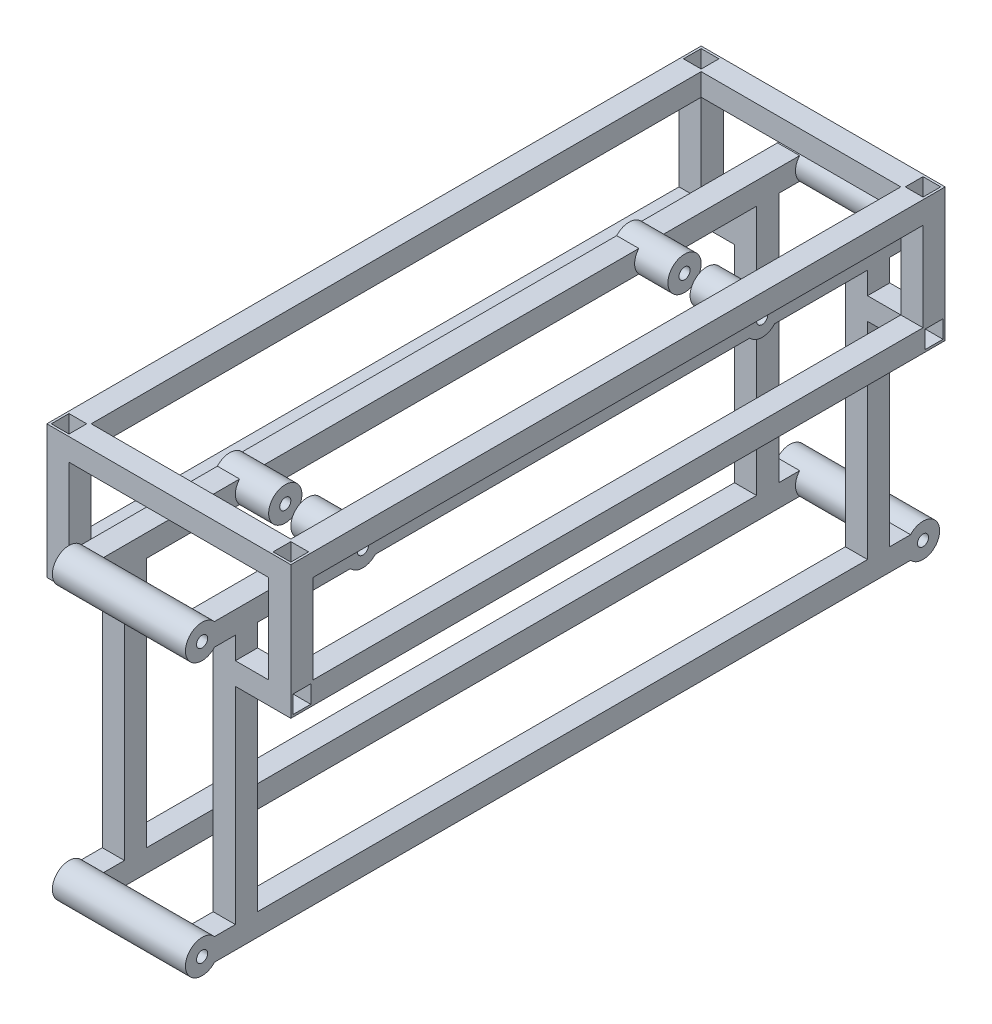
SolidWorks part; units mm, degrees
ref_plane "Płaszczyzna przednia" through (0, 0, 0) normal (0, 0, 1) x (1, 0, 0)
ref_plane "Płaszczyzna górna" through (0, 0, 0) normal (0, 1, 0) x (1, 0, 0)
ref_plane "Płaszczyzna prawa" through (0, 0, 0) normal (1, 0, 0) x (0, 0, -1)
sketch "Szkic1" plane through (0, 0, 0) normal (0, 0, 1) x (1, 0, 0)
  line L0 (-8, -8) -> (-8, 8)
  line L1 (-10, -10) -> (10, -10)
  line L2 (-10, -10) -> (-10, 10)
  line L3 (-10, 10) -> (10, 10)
  line L4 (10, -10) -> (10, 10)
  line L5 (-10, -10) -> (10, 10) construction
  line L6 (-10, 10) -> (10, -10) construction
  line L7 (-110, -10) -> (-90, -10)
  line L8 (-110, -10) -> (-110, 10)
  line L9 (-110, 10) -> (-90, 10)
  line L10 (-90, -10) -> (-90, 10)
  line L11 (-110, -10) -> (-90, 10) construction
  line L12 (-110, 10) -> (-90, -10) construction
  line L13 (-8, 8) -> (8, 8)
  line L14 (8, -8) -> (8, 8)
  line L15 (-8, -8) -> (8, -8)
  line L16 (-92, -8) -> (-92, 8)
  line L17 (-108, 8) -> (-92, 8)
  line L18 (-108, -8) -> (-108, 8)
  line L19 (-108, -8) -> (-92, -8)
  point P1 (0, 0)
  point P6 (-100, 0)
  dimension "D1" = 20
  dimension "D2" = 20
  dimension "D3" = 100
  dimension "D4" = 20
  dimension "D5" = 20
  dimension "D6" = 2
extrude "Dodanie-wyciągnięcie1" add sketch "Szkic1" along normal mid plane 650
sketch "Szkic3" plane through (10, 0, 0) normal (1, 0, 0) x (0, 0, -1)
  line L0 (-325, -10) -> (-325, 10) construction
  circle A1 centre (-325, 0) radius 15
  dimension "D1" = 30
extrude "Dodanie-wyciągnięcie2" add sketch "Szkic3" against normal blind 120
sketch "Szkic4" plane through (10, 0, 0) normal (1, 0, 0) x (0, 0, -1)
  circle A0 centre (-325, 0) radius 5
  dimension "D1" = 10
extrude "Wytnij-wyciągnięcie1" cut sketch "Szkic4" against normal blind 120
mirror "Lustro1" about plane through (0, 0, 0) normal (0, 0, 1) of "Wytnij-wyciągnięcie1", "Dodanie-wyciągnięcie2"
sketch "Szkic5" plane through (0, 10, 0) normal (0, 1, 0) x (1, 0, 0)
  line L0 (-10, -313.8197) -> (-10, 313.8197) construction
  line L1 (-10, -295) -> (10, -295)
  line L2 (-10, -295) -> (-10, -275)
  line L3 (-10, -275) -> (10, -275)
  line L4 (10, -295) -> (10, -275)
  line L5 (10, -313.8197) -> (10, 313.8197) construction
  line L6 (-110, -313.8197) -> (-110, 313.8197) construction
  line L7 (-110, -295) -> (-90, -295)
  line L8 (-110, -295) -> (-110, -275)
  line L9 (-110, -275) -> (-90, -275)
  line L10 (-90, -295) -> (-90, -275)
  line L11 (-90, -313.8197) -> (-90, 313.8197) construction
  line L16 (-108, -277) -> (-92, -277)
  line L17 (-92, -293) -> (-92, -277)
  line L18 (-108, -293) -> (-92, -293)
  line L19 (-108, -293) -> (-108, -277)
  line L20 (-8, -277) -> (8, -277)
  line L21 (8, -293) -> (8, -277)
  line L22 (-8, -293) -> (8, -293)
  line L23 (-8, -293) -> (-8, -277)
  line L24 (-55, 0) -> (55, 0) construction
  dimension "D1" = 20
  dimension "D2" = 20
  dimension "D5" = 275
  dimension "D6" = 275
  dimension "D3" = 2
  dimension "D4" = 2
extrude "Dodanie-wyciągnięcie3" add sketch "Szkic5" along normal blind 226
mirror "Lustro2" about plane through (0, 0, 0) normal (0, 0, 1) of "Dodanie-wyciągnięcie3"
ref_plane "Płaszczyzna1" through (0, 123, 0) normal (0, 1, 0) x (1, 0, 0)
sketch "Szkic6" plane through (0, 0, 0) normal (0, 0, 1) x (1, 0, 0)
  line L0 (8, 238) -> (8, 254)
  line L1 (-10, 236) -> (10, 236)
  line L2 (-10, 236) -> (-10, 256)
  line L3 (-10, 256) -> (10, 256)
  line L4 (10, 236) -> (10, 256)
  line L5 (-8, 254) -> (8, 254)
  line L6 (-8, 238) -> (-8, 254)
  line L7 (-8, 238) -> (8, 238)
  line L9 (-108, 254) -> (-92, 254)
  line L10 (-110, 236) -> (-90, 236)
  line L11 (-110, 236) -> (-110, 256)
  line L12 (-110, 256) -> (-90, 256)
  line L13 (-90, 236) -> (-90, 256)
  line L14 (-92, 238) -> (-92, 254)
  line L15 (-108, 238) -> (-92, 238)
  line L16 (-108, 238) -> (-108, 254)
  dimension "D1" = 20
  dimension "D3" = 20
  dimension "D4" = 20
  dimension "D2" = 2
  dimension "D5" = 2
extrude "Dodanie-wyciągnięcie4" add sketch "Szkic6" along normal mid plane 650
sketch "Szkic7" plane through (10, 0, 0) normal (1, 0, 0) x (0, 0, -1)
  line L0 (-325, 236) -> (-325, 256) construction
  circle A0 centre (-325, 246) radius 15
  dimension "D1" = 30
extrude "Dodanie-wyciągnięcie5" add sketch "Szkic7" against normal blind 120
sketch "Szkic8" plane through (10, 0, 0) normal (1, 0, 0) x (0, 0, -1)
  circle A0 centre (-325, 246) radius 5
  dimension "D1" = 10
extrude "Wytnij-wyciągnięcie2" cut sketch "Szkic8" against normal blind 120
mirror "Lustro4" about plane through (0, 0, 0) normal (0, 0, 1) of "Dodanie-wyciągnięcie5", "Wytnij-wyciągnięcie2"
sketch "Szkic9" plane through (10, 0, 0) normal (1, 0, 0) x (0, 0, -1)
  line L0 (-275, 236) -> (275, 236) construction
  line L1 (-275, 236) -> (-275, 10) construction
  circle A0 centre (-180, 246) radius 15
  circle A1 centre (-180, 246) radius 5
  dimension "D2" = 30
  dimension "D3" = 10
  dimension "D1" = 10
  dimension "D4" = 95
extrude "Dodanie-wyciągnięcie6" add sketch "Szkic9" against normal blind 120 contours A0
sketch "Szkic10" plane through (10, 0, 0) normal (1, 0, 0) x (0, 0, -1)
  circle A0 centre (-180, 246) radius 5
  dimension "D1" = 10
extrude "Wytnij-wyciągnięcie3" cut sketch "Szkic10" against normal blind 120
sketch "Szkic11" plane through (0, 256, 0) normal (0, 1, 0) x (1, 0, 0)
  line L0 (-10, -168.8197) -> (-10, 313.8197) construction
  line L1 (-60, -300) -> (-40, -300)
  line L2 (-60, -300) -> (-60, 0)
  line L3 (-60, 0) -> (-40, 0)
  line L4 (-40, -300) -> (-40, 0)
  line L5 (-60, -300) -> (-40, 0) construction
  line L6 (-60, 0) -> (-40, -300) construction
  line L7 (-66, 0) -> (66, 0) construction
  point P0 (-50, -150)
  dimension "D1" = 20
  dimension "D2" = 30
  dimension "D3" = 0
  dimension "D4" = 300
extrude "Wytnij-wyciągnięcie4" cut sketch "Szkic11" against normal mid plane 120
sketch "Szkic12" plane through (10, 0, 0) normal (1, 0, 0) x (0, 0, -1)
  line L0 (275, 236) -> (275, 10) construction
  line L1 (-168.8197, 236) -> (275, 236) construction
  circle A0 centre (180, 246) radius 15
  dimension "D2" = 30
  dimension "D1" = 95
  dimension "D3" = 10
extrude "Dodanie-wyciągnięcie7" add sketch "Szkic12" against normal blind 120
sketch "Szkic13" plane through (10, 0, 0) normal (1, 0, 0) x (0, 0, -1)
  circle A0 centre (180, 246) radius 5
  dimension "D1" = 10
extrude "Wytnij-wyciągnięcie5" cut sketch "Szkic13" against normal blind 120
sketch "Szkic14" plane through (0, 256, 0) normal (0, 1, 0) x (1, 0, 0)
  line L0 (-110, 191.1803) -> (-110, 313.8197) construction
  line L1 (-60, 0) -> (-40, 0)
  line L2 (-60, 0) -> (-60, 300)
  line L3 (-60, 300) -> (-40, 300)
  line L4 (-40, 0) -> (-40, 300)
  line L5 (-60, 0) -> (-40, 300) construction
  line L6 (-60, 300) -> (-40, 0) construction
  line L7 (-66, 0) -> (66, 0) construction
  point P0 (-50, 150)
  dimension "D1" = 20
  dimension "D2" = 50
  dimension "D3" = 300
  dimension "D4" = 0
extrude "Wytnij-wyciągnięcie6" cut sketch "Szkic14" along normal mid plane 120
sketch "Szkic15" plane through (10, 0, 0) normal (1, 0, 0) x (0, 0, -1)
  line L0 (275, 236) -> (275, 10) construction
  line L1 (275, 216) -> (295, 216)
  line L2 (275, 216) -> (275, 196)
  line L3 (275, 196) -> (295, 196)
  line L4 (295, 216) -> (295, 196)
  line L5 (295, 236) -> (295, 10) construction
  line L7 (191.1803, 256) -> (313.8197, 256) construction
  line L8 (277, 214) -> (293, 214)
  line L9 (293, 214) -> (293, 198)
  line L10 (277, 198) -> (293, 198)
  line L11 (277, 214) -> (277, 198)
  dimension "D1" = 20
  dimension "D2" = 40
  dimension "D3" = 2
extrude "Dodanie-wyciągnięcie8" add sketch "Szkic15" along normal blind 50
mirror "Lustro5" about plane through (0, 0, 0) normal (0, 0, 1) of "Dodanie-wyciągnięcie8"
sketch "Szkic16" plane through (0, 0, -275) normal (0, 0, 1) x (1, 0, 0)
  line L0 (60, 196) -> (10, 196) construction
  line L1 (60, 216) -> (40, 216)
  line L2 (60, 216) -> (60, 196)
  line L3 (60, 196) -> (40, 196)
  line L4 (40, 216) -> (40, 196)
  line L5 (58, 214) -> (42, 214)
  line L6 (42, 214) -> (42, 198)
  line L7 (58, 198) -> (42, 198)
  line L8 (58, 214) -> (58, 198)
  dimension "D1" = 20
  dimension "D2" = 2
extrude "Dodanie-wyciągnięcie9" add sketch "Szkic16" along normal up to next
ref_plane "Płaszczyzna2" through (-50, 0, 0) normal (1, 0, 0) x (0, 0, -1)
mirror "Lustro6" about plane through (-50, 0, 0) normal (1, 0, 0) of "Dodanie-wyciągnięcie9", "Dodanie-wyciągnięcie8", "Lustro5"
sketch "Szkic17" plane through (0, 216, 0) normal (0, 1, 0) x (1, 0, 0)
  line L0 (58, 293) -> (42, 293)
  line L1 (60, 295) -> (40, 295)
  line L2 (60, 295) -> (60, 275)
  line L3 (60, 275) -> (40, 275)
  line L4 (40, 295) -> (40, 275)
  line L5 (42, 293) -> (42, 277)
  line L6 (58, 277) -> (42, 277)
  line L7 (58, 293) -> (58, 277)
  line L8 (-66, 0) -> (66, 0) construction
  line L9 (40, -295) -> (40, -275)
  line L10 (60, -275) -> (40, -275)
  line L11 (60, -295) -> (60, -275)
  line L12 (58, -293) -> (58, -277)
  line L13 (58, -293) -> (42, -293)
  line L14 (60, -295) -> (40, -295)
  line L15 (42, -293) -> (42, -277)
  line L16 (58, -277) -> (42, -277)
  line L17 (-50, -11) -> (-50, 11) construction
  line L18 (-158, 293) -> (-158, 277)
  line L19 (-158, 277) -> (-142, 277)
  line L20 (-142, 293) -> (-142, 277)
  line L21 (-140, 295) -> (-140, 275)
  line L22 (-160, 275) -> (-140, 275)
  line L23 (-160, 295) -> (-160, 275)
  line L24 (-160, 295) -> (-140, 295)
  line L25 (-158, 293) -> (-142, 293)
  line L26 (-158, -277) -> (-142, -277)
  line L27 (-142, -293) -> (-142, -277)
  line L28 (-160, -295) -> (-140, -295)
  line L29 (-158, -293) -> (-142, -293)
  line L30 (-158, -293) -> (-158, -277)
  line L31 (-160, -295) -> (-160, -275)
  line L32 (-160, -275) -> (-140, -275)
  line L33 (-140, -295) -> (-140, -275)
  dimension "D1" = 2
extrude "Dodanie-wyciągnięcie10" add sketch "Szkic17" along normal blind 100
ref_plane "Płaszczyzna3" through (0, 0, 380) normal (0, 0, 1) x (1, 0, 0)
sketch "Szkic19" plane through (0, 0, 275) normal (0, 0, -1) x (-1, 0, 0)
  line L0 (160, 196) -> (160, 316) construction
  line L1 (140, 316) -> (160, 316)
  line L2 (140, 316) -> (140, 296)
  line L3 (140, 296) -> (160, 296)
  line L4 (160, 316) -> (160, 296)
  line L5 (142, 314) -> (158, 314)
  line L6 (158, 314) -> (158, 298)
  line L7 (142, 298) -> (158, 298)
  line L8 (142, 314) -> (142, 298)
  dimension "D1" = 20
  dimension "D2" = 2
extrude "Dodanie-wyciągnięcie11" add sketch "Szkic19" along normal up to next
mirror "Lustro7" about plane through (-50, 0, 0) normal (1, 0, 0) of "Dodanie-wyciągnięcie11"
sketch "Szkic20" plane through (-140, 0, 0) normal (1, 0, 0) x (0, 0, -1)
  line L0 (293, 314) -> (293, 298)
  line L1 (295, 316) -> (275, 316)
  line L2 (295, 316) -> (295, 296)
  line L3 (295, 296) -> (275, 296)
  line L4 (275, 316) -> (275, 296)
  line L5 (293, 298) -> (277, 298)
  line L6 (277, 314) -> (277, 298)
  line L7 (293, 314) -> (277, 314)
  dimension "D1" = 2
extrude "Dodanie-wyciągnięcie12" add sketch "Szkic20" along normal up to next
mirror "Lustro8" about plane through (0, 0, 0) normal (0, 0, 1) of "Dodanie-wyciągnięcie12"
